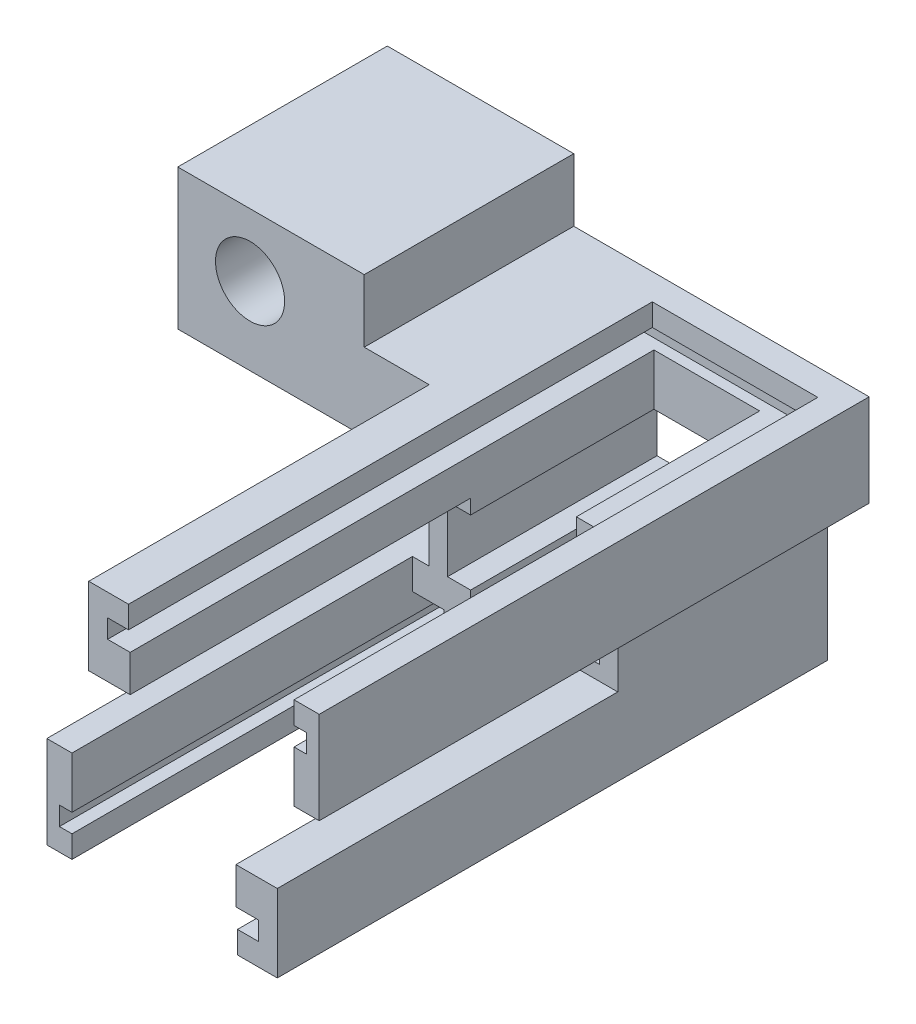
SolidWorks part; units mm, degrees
ref_plane "Front Plane" through (0, 0, 0) normal (0, 0, 1) x (1, 0, 0)
ref_plane "Top Plane" through (0, 0, 0) normal (0, 1, 0) x (1, 0, 0)
ref_plane "Right Plane" through (0, 0, 0) normal (1, 0, 0) x (0, 0, -1)
sketch "Sketch2" plane through (0, 0, 0) normal (0, 0, 1) x (1, 0, 0)
  line L0 (13, 0) -> (9.6353, 0) construction
  line L1 (-13, 11.9) -> (13, 11.9)
  line L2 (-13, 11.9) -> (-13, -11.9)
  line L3 (-13, -11.9) -> (13, -11.9)
  line L4 (13, 11.9) -> (13, -11.9)
  line L5 (0, -11.9) -> (0, -9.4467) construction
  dimension "D1" = 26
  dimension "D2" = 23.8
  dimension "D3" = 0
  dimension "D4" = 0
extrude "Boss-Extrude1" add sketch "Sketch2" along normal blind 20
sketch "Sketch3" plane through (0, 0, 20) normal (0, 0, 1) x (1, 0, 0)
  line L0 (13, 11.9) -> (-13, 11.9) construction
  line L1 (-7.25, 3.1) -> (7.25, 3.1)
  line L2 (-7.25, 3.1) -> (-7.25, -3.1)
  line L3 (-7.25, -3.1) -> (7.25, -3.1)
  line L4 (7.25, 3.1) -> (7.25, -3.1)
  line L5 (0, 11.9) -> (0, 9.3814) construction
  line L6 (13, -11.9) -> (13, 11.9) construction
  line L7 (13, 0) -> (11.1901, 0) construction
  line L8 (0, 3.1) -> (0, 0.3121) construction
  line L9 (7.25, 0) -> (5.279, 0) construction
  dimension "D1" = 14.5
  dimension "D2" = 6.2
  dimension "D3" = 0
  dimension "D4" = 0
sketch "Sketch4" plane through (0, 0, 20) normal (0, 0, 1) x (1, 0, 0)
  line L0 (0, 8) -> (0, 5.7772) construction
  line L1 (-5.045, 8) -> (5.045, 8)
  line L2 (-5.045, 8) -> (-5.045, 3.1)
  line L3 (-5.045, 3.1) -> (5.045, 3.1)
  line L4 (5.045, 8) -> (5.045, 3.1)
  line L5 (5.045, 5.55) -> (3.7199, 5.55) construction
  line L6 (-7.25, 3.1) -> (7.25, 3.1) construction
  dimension "D1" = 10.09
  dimension "D2" = 4.9
  dimension "D3" = 0
  dimension "D4" = 0
sketch "Sketch5" plane through (0, 0, 20) normal (0, 0, 1) x (1, 0, 0)
  line L0 (0, -8) -> (0, -5.7667) construction
  line L1 (-5.045, -3.1) -> (5.045, -3.1)
  line L2 (-5.045, -3.1) -> (-5.045, -8)
  line L3 (-5.045, -8) -> (5.045, -8)
  line L4 (5.045, -3.1) -> (5.045, -8)
  line L5 (-7.25, -3.1) -> (7.25, -3.1) construction
  dimension "D1" = 10.09
  dimension "D2" = 4.9
  dimension "D3" = 0
  dimension "D4" = 0
sketch "Sketch6" plane through (0, 0, 20) normal (0, 0, 1) x (1, 0, 0)
  line L0 (2.3, 8) -> (2.3, 8.2761) construction
  line L1 (-7.2, 9.78) -> (11.8, 9.78)
  line L2 (-7.2, 9.78) -> (-7.2, 8)
  line L3 (-7.2, 8) -> (11.8, 8)
  line L4 (11.8, 9.78) -> (11.8, 8)
  line L5 (-5.045, 8) -> (5.045, 8) construction
  dimension "D1" = 19
  dimension "D2" = 1.78
  dimension "D3" = 7.2
  dimension "D4" = 0
sketch "Sketch7" plane through (0, 0, 20) normal (0, 0, 1) x (1, 0, 0)
  line L0 (-2.3, -8) -> (-2.3, -8.827) construction
  line L1 (-11.8, -8) -> (7.2, -8)
  line L2 (-11.8, -8) -> (-11.8, -9.78)
  line L3 (-11.8, -9.78) -> (7.2, -9.78)
  line L4 (7.2, -8) -> (7.2, -9.78)
  line L5 (-5.045, -8) -> (5.045, -8) construction
  dimension "D1" = 7.2
  dimension "D2" = 0
  dimension "D3" = 19
  dimension "D4" = 1.78
sketch "Sketch9" plane through (0, 0, 20) normal (0, 0, 1) x (1, 0, 0)
  line L0 (13, 11.9) -> (-13, 11.9) construction
  line L1 (-5.2, 11.9) -> (10.6, 11.9)
  line L2 (-5.2, 11.9) -> (-5.2, 9.78)
  line L3 (-5.2, 9.78) -> (10.6, 9.78)
  line L4 (10.6, 11.9) -> (10.6, 9.78)
  line L5 (-7.2, 9.78) -> (11.8, 9.78) construction
  dimension "D1" = 2
  dimension "D2" = 1.2
  dimension "D3" = 0
  dimension "D4" = 0
sketch "Sketch10" plane through (0, 0, 20) normal (0, 0, 1) x (1, 0, 0)
  line L0 (-7.2, 8) -> (11.8, 8) construction
  line L1 (7.6, 8) -> (10.6, 8)
  line L2 (7.6, 8) -> (7.6, 6)
  line L3 (7.6, 6) -> (10.6, 6)
  line L4 (10.6, 8) -> (10.6, 6)
  dimension "D1" = 1.2
  dimension "D2" = 3
  dimension "D3" = 2
  dimension "D4" = 0
sketch "Sketch11" plane through (0, 0, 20) normal (0, 0, 1) x (1, 0, 0)
  line L0 (-11.8, -8) -> (7.2, -8) construction
  line L1 (-10.6, -6) -> (-7.6, -6)
  line L2 (-10.6, -6) -> (-10.6, -8)
  line L3 (-10.6, -8) -> (-7.6, -8)
  line L4 (-7.6, -6) -> (-7.6, -8)
  dimension "D1" = 3
  dimension "D2" = 2
  dimension "D3" = 1.2
  dimension "D4" = 0
sketch "Sketch12" plane through (0, 0, 20) normal (0, 0, 1) x (1, 0, 0)
  line L0 (-11.8, -9.78) -> (7.2, -9.78) construction
  line L1 (-10.6, -9.78) -> (5.2, -9.78)
  line L2 (-10.6, -9.78) -> (-10.6, -11.9)
  line L3 (-10.6, -11.9) -> (5.2, -11.9)
  line L4 (5.2, -9.78) -> (5.2, -11.9)
  line L5 (-13, -11.9) -> (13, -11.9) construction
  dimension "D1" = 2
  dimension "D2" = 1.2
  dimension "D3" = 0
  dimension "D4" = 0
extrude "Cut-Extrude1" cut sketch "Sketch3" against normal blind 20
extrude "Cut-Extrude2" cut sketch "Sketch4" against normal blind 17.5
extrude "Cut-Extrude3" cut sketch "Sketch5" against normal blind 17.5
extrude "Cut-Extrude4" cut sketch "Sketch10" against normal blind 17.5
extrude "Cut-Extrude5" cut sketch "Sketch11" against normal blind 17.5
extrude "Cut-Extrude6" cut sketch "Sketch7" against normal blind 18.5
extrude "Cut-Extrude7" cut sketch "Sketch6" against normal blind 18.5
extrude "Cut-Extrude8" cut sketch "Sketch9" against normal blind 17.5
extrude "Cut-Extrude9" cut sketch "Sketch12" against normal blind 17.5
sketch "Sketch13" plane through (-13, 0, 0) normal (-1, 0, 0) x (0, 0, 1)
  line L0 (20, 11.9) -> (20, -11.9) construction
  line L1 (20, 17.9) -> (0, 17.9)
  line L2 (20, 17.9) -> (20, 5.9)
  line L3 (20, 5.9) -> (0, 5.9)
  line L4 (0, 17.9) -> (0, 5.9)
  line L5 (0, 11.9) -> (0, -11.9) construction
  line L6 (0, 11.9) -> (3.0794, 11.9) construction
  dimension "D1" = 12
  dimension "D2" = 0
  dimension "D3" = 0
  dimension "D4" = 0
sketch "Sketch14" plane through (0, 11.9, 0) normal (0, 1, 0) x (1, 0, 0)
  line L0 (-5.2, -20) -> (-13, -20) construction
  line L1 (-5.2, -20) -> (-13, -20)
  line L2 (-5.2, -20) -> (-5.2, 0)
  line L3 (-5.2, 0) -> (-13, 0)
  line L4 (-13, -20) -> (-13, 0)
  line L5 (13, 0) -> (-13, 0) construction
  line L6 (-13, 0) -> (-13, -3.0794) construction
  dimension "D1" = 0
  dimension "D2" = 0
  dimension "D3" = 0
  dimension "D4" = 0
extrude "Boss-Extrude2" add sketch "Sketch14" along normal blind 6
extrude "Boss-Extrude3" add sketch "Sketch13" along normal blind 20
sketch "Sketch15" plane through (0, 0, 20) normal (0, 0, 1) x (1, 0, 0)
  line L0 (-33, 5.9) -> (-33, 17.9) construction
  line L1 (-33, 11.9) -> (-26.1, 11.9) construction
  line L3 (-33, 17.9) -> (-5.2, 17.9) construction
  circle A0 centre (-26.1, 11.9) radius 3.3
  point P6 (-19.1, 17.9)
  dimension "D1" = 6.6
  dimension "D2" = 0
  dimension "D3" = 7
extrude "Cut-Extrude10" cut sketch "Sketch15" against normal blind 19
sketch "Sketch16" plane through (0, 0, 20) normal (0, 0, 1) x (1, 0, 0)
  line L1 (9, 3.1) -> (13, 3.1)
  line L2 (9, 3.1) -> (9, -11.9)
  line L3 (9, -11.9) -> (13, -11.9)
  line L4 (13, 3.1) -> (13, -11.9)
  dimension "D1" = 4
  dimension "D2" = 15
extrude "Cut-Extrude11" cut sketch "Sketch16" against normal blind 20
sketch "Sketch18" plane through (0, 0, 20) normal (0, 0, 1) x (1, 0, 0)
  line L1 (-13, 5.9) -> (-9, 5.9)
  line L2 (-13, 5.9) -> (-13, -3.1)
  line L3 (-13, -3.1) -> (-9, -3.1)
  line L4 (-9, 5.9) -> (-9, -3.1)
  dimension "D1" = 4
  dimension "D2" = 9
extrude "Cut-Extrude12" cut sketch "Sketch18" against normal blind 20
sketch "Sketch21" plane through (0, 0, 20) normal (0, 0, 1) x (1, 0, 0)
  line L0 (-13, -11.9) -> (-13, -3.1)
  line L2 (-13, -3.1) -> (-10.6, -3.1)
  line L3 (-13, -11.9) -> (-10.6, -11.9)
  line L4 (-10.6, -11.9) -> (-10.6, -9.78)
  line L5 (-10.6, -9.78) -> (-10.6, -11.9) construction
  line L6 (-10.6, -9.78) -> (-11.8, -9.78)
  line L7 (-11.8, -9.78) -> (-10.6, -9.78) construction
  line L8 (-11.8, -9.78) -> (-11.8, -8)
  line L9 (-11.8, -8) -> (-11.8, -9.78) construction
  line L10 (-11.8, -8) -> (-10.6, -8)
  line L11 (5.2, -9.78) -> (5.2, -11.9)
  line L12 (5.2, -11.9) -> (5.2, -9.78) construction
  line L13 (5.2, -11.9) -> (9, -11.9)
  line L14 (9, -11.9) -> (9, -4.5)
  line L15 (9, 3.1) -> (9, -11.9) construction
  line L16 (9, -4.5) -> (5.045, -4.5)
  line L17 (5.045, -8) -> (5.045, -3.1) construction
  line L18 (5.045, -4.5) -> (5.045, -8)
  line L19 (5.045, -8) -> (7.2, -8)
  line L20 (7.2, -8) -> (7.2, -9.78)
  line L21 (7.2, -9.78) -> (5.2, -9.78)
  line L23 (-13, -3.1) -> (-9, -3.1) construction
  line L24 (-10.6, -3.1) -> (-10.6, -8)
  dimension "D1" = 3.5
extrude "Boss-Extrude8" add sketch "Sketch21" along normal blind 32.5
sketch "Sketch22" plane through (0, 0, 20) normal (0, 0, 1) x (1, 0, 0)
  line L0 (10.6, 11.9) -> (13, 11.9)
  line L1 (13, 11.9) -> (13, 3.1)
  line L2 (13, 3.1) -> (10.6, 3.1)
  line L3 (13, 3.1) -> (9, 3.1) construction
  line L4 (10.6, 3.1) -> (10.6, 8)
  line L5 (10.6, 8) -> (11.8, 8)
  line L6 (11.8, 8) -> (11.8, 9.78)
  line L7 (11.8, 9.78) -> (10.6, 9.78)
  line L8 (10.6, 9.78) -> (10.6, 11.9)
  line L9 (-5.2, 9.78) -> (-5.2, 11.9)
  line L10 (-5.2, 17.9) -> (-5.2, 9.78) construction
  line L11 (-5.2, 11.9) -> (-9, 11.9)
  line L12 (-9, 11.9) -> (-9, 4.5)
  line L13 (-9, -3.1) -> (-9, 5.9) construction
  line L14 (-9, 4.5) -> (-5.045, 4.5)
  line L15 (-5.045, 8) -> (-5.045, 3.1) construction
  line L16 (-5.045, 4.5) -> (-5.045, 8)
  line L17 (-5.045, 8) -> (-7.2, 8)
  line L18 (-7.2, 8) -> (-5.045, 8) construction
  line L19 (-7.2, 8) -> (-7.2, 9.78)
  line L20 (-7.2, 9.78) -> (-5.2, 9.78)
  dimension "D1" = 3.8
  dimension "D2" = 7.4
  dimension "D3" = 3.5
extrude "Boss-Extrude9" add sketch "Sketch22" along normal blind 32.5
sketch "Sketch23" plane through (0, 17.9, 0) normal (0, 1, 0) x (1, 0, 0)
  line L0 (-5.2, 0) -> (-33, 0) construction
  line L1 (-15.2, 0) -> (-5.2, 0)
  line L2 (-15.2, 0) -> (-15.2, -20)
  line L3 (-15.2, -20) -> (-5.2, -20)
  line L4 (-5.2, 0) -> (-5.2, -20)
  line L5 (-5.2, -20) -> (-5.2, 0) construction
  line L6 (-33, -20) -> (-5.2, -20) construction
  dimension "D1" = 0
  dimension "D2" = 0
  dimension "D3" = 10
extrude "Cut-Extrude14" cut sketch "Sketch23" against normal blind 6
sketch "Sketch24" plane through (0, 5.9, 0) normal (0, -1, 0) x (1, 0, 0)
  line L0 (-33, 0) -> (-9, 0) construction
  line L1 (-33, 20) -> (-9, 20)
  line L2 (-33, 20) -> (-33, 0)
  line L3 (-33, 0) -> (-9, 0)
  line L4 (-9, 20) -> (-9, 0)
  line L5 (-9, 0) -> (-9, 20) construction
extrude "Boss-Extrude10" add sketch "Sketch24" along normal blind 1.4
sketch "Sketch26" plane through (0, 0, 0) normal (0, 0, -1) x (-1, 0, 0)
  circle A0 centre (26.1, 11.9) radius 1.45
  dimension "D1" = 2.9
  dimension "D2" = 6.9
  dimension "D3" = 6
extrude "Cut-Extrude15" cut sketch "Sketch26" against normal blind 10
